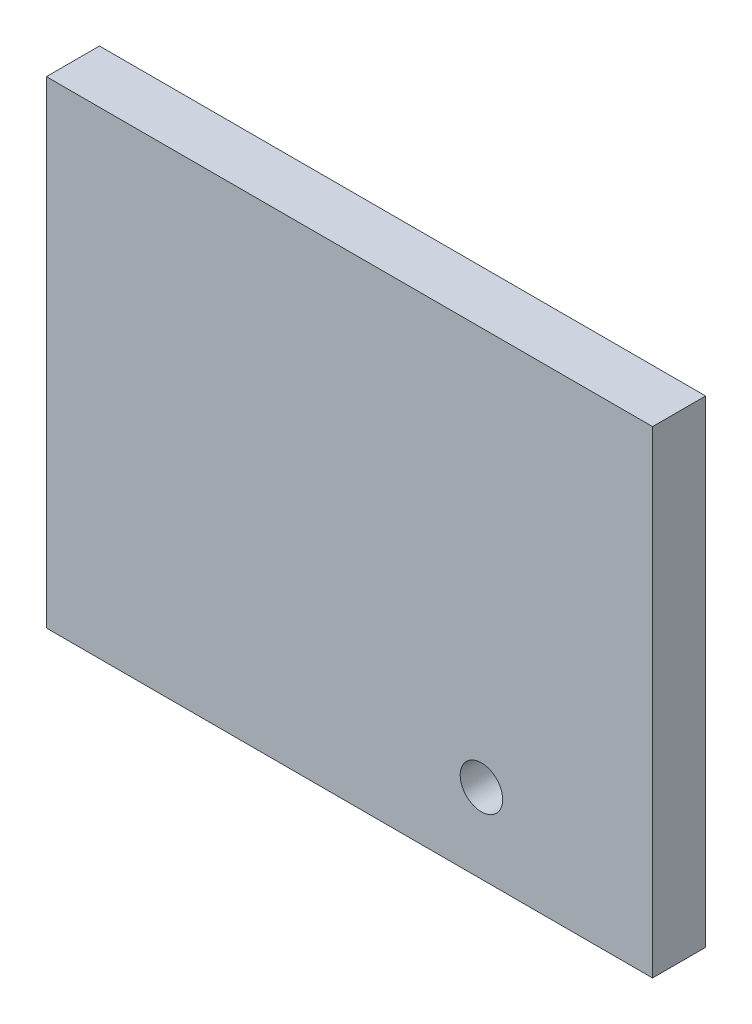
SolidWorks part; units mm, degrees
material "Balsa"
ref_plane "Plan de face" through (0, 0, 0) normal (0, 0, 1) x (1, 0, 0)
ref_plane "Plan de dessus" through (0, 0, 0) normal (0, 1, 0) x (1, 0, 0)
ref_plane "Plan de droite" through (0, 0, 0) normal (1, 0, 0) x (0, 0, -1)
sketch "Sketch1" plane through (0, 0, 0) normal (0, 0, 1) x (1, 0, 0)
  line L1 (-57.12, -5) -> (57.12, -5)
  line L2 (-57.12, -5) -> (-57.12, 5)
  line L3 (-57.12, 5) -> (57.12, 5)
  line L4 (57.12, -5) -> (57.12, 5)
  line L5 (-57.12, -5) -> (57.12, 5) construction
  line L6 (-57.12, 5) -> (57.12, -5) construction
  point P0 (0, 0)
  dimension "D1" = 10
  dimension "D2" = 114.24
extrude "Boss-Extrude1" add sketch "Sketch1" along normal blind 10
sketch "Sketch3" plane through (0, 5, 0) normal (0, 1, 0) x (1, 0, 0)
  line L1 (-57.12, 0) -> (57.12, 0)
  line L2 (-57.12, 0) -> (-57.12, -10)
  line L3 (-57.12, -10) -> (57.12, -10)
  line L4 (57.12, 0) -> (57.12, -10)
extrude "Boss-Extrude2" add sketch "Sketch3" along normal blind 80
sketch "Sketch4" plane through (0, 0, 10) normal (0, 0, 1) x (1, 0, 0)
  line L0 (-57.12, -5) -> (57.12, -5) construction
  line L1 (57.12, -5) -> (57.12, 85) construction
  circle A0 centre (24.87, 9.99) radius 4
  dimension "D1" = 8
  dimension "D2" = 14.99
  dimension "D3" = 32.25
extrude "Cut-Extrude1" cut sketch "Sketch4" against normal through all
